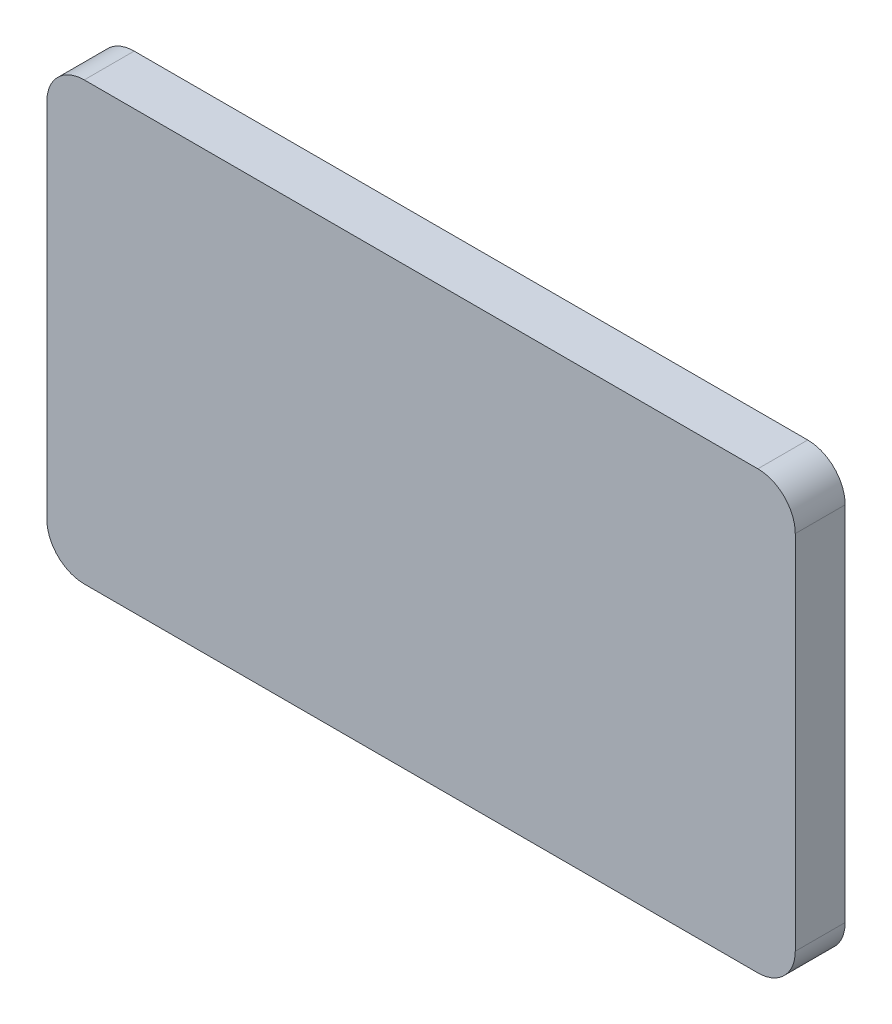
SolidWorks part; units mm, degrees
ref_plane "Front Plane" through (0, 0, 0) normal (0, 0, 1) x (1, 0, 0)
ref_plane "Top Plane" through (0, 0, 0) normal (0, 1, 0) x (1, 0, 0)
ref_plane "Right Plane" through (0, 0, 0) normal (1, 0, 0) x (0, 0, -1)
sketch "Sketch2" plane through (0, 0, 0) normal (0, 0, 1) x (1, 0, 0)
  line L1 (0, 0) -> (190.5, 0)
  line L2 (0, 0) -> (0, 111.125)
  line L3 (0, 111.125) -> (190.5, 111.125)
  line L4 (190.5, 0) -> (190.5, 111.125)
  dimension "D1" = 190.5
  dimension "D2" = 111.125
extrude "Boss-Extrude1" add sketch "Sketch2" along normal blind 12.7
fillet "Fillet1" radius 9.525 4 edges at (0, 0, 6.35) (190.5, 0, 6.35) (190.5, 111.125, 6.35) (0, 111.125, 6.35)
ref_plane "Plane1" through (0, 55.5625, 0) normal (0, 1, 0) x (1, 0, 0)
